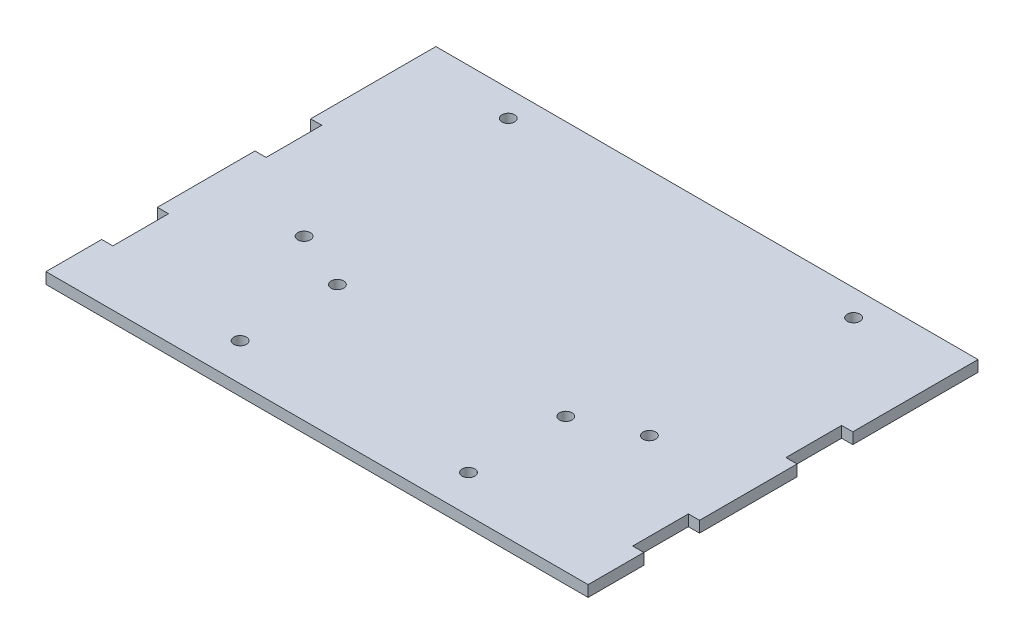
SolidWorks part; units mm, degrees
other "Markup1"
sketch "Sketch3" plane through (-73, 3, -52.5) normal (0, 1, 0) x (1, 0, 0)
ref_plane "Front Plane" through (0, 0, 0) normal (0, 0, 1) x (1, 0, 0)
ref_plane "Top Plane" through (0, 0, 0) normal (0, 1, 0) x (1, 0, 0)
ref_plane "Right Plane" through (0, 0, 0) normal (1, 0, 0) x (0, 0, -1)
other "Configuration Table"
sketch "Sketch1" plane through (0, 0, 0) normal (0, 1, 0) x (1, 0, 0)
  line L1 (73, -52.5) -> (-73, -52.5)
  line L2 (73, -52.5) -> (73, 52.5)
  line L3 (73, 52.5) -> (-73, 52.5)
  line L4 (-73, -52.5) -> (-73, 52.5)
  line L5 (73, -52.5) -> (-73, 52.5) construction
  line L6 (73, 52.5) -> (-73, -52.5) construction
  point P0 (0, 0)
  dimension "D1" = 105
  dimension "D2" = 146
extrude "Boss-Extrude1" add sketch "Sketch1" along normal blind 3
sketch "Sketch2" plane through (0, 3, 0) normal (0, 1, 0) x (1, 0, 0)
  line L0 (73, 52.5) -> (-73, 52.5) construction
  line L1 (-73, -37.5) -> (-70, -37.5)
  line L2 (-73, 52.5) -> (-73, -52.5) construction
  line L3 (-70, -37.5) -> (-70, -22.5)
  line L4 (-70, -22.5) -> (-73, -22.5)
  line L5 (-73, -22.5) -> (-73, -37.5)
  line L6 (-73, 3.77) -> (-70, 3.77)
  line L7 (-70, 3.77) -> (-70, 18.77)
  line L8 (-70, 18.77) -> (-73, 18.77)
  line L9 (-73, 18.77) -> (-73, 3.77)
  line L10 (73, 18.77) -> (70, 18.77)
  line L11 (73, -52.5) -> (73, 52.5) construction
  line L12 (70, 18.77) -> (70, 3.77)
  line L13 (70, 3.77) -> (73, 3.77)
  line L14 (73, 3.77) -> (73, 18.77)
  line L15 (73, -22.5) -> (70, -22.5)
  line L16 (70, -22.5) -> (70, -37.5)
  line L17 (70, -37.5) -> (73, -37.5)
  line L18 (73, -37.5) -> (73, -22.5)
  circle A0 centre (-46.5, 45.5) radius 1.7
  circle A1 centre (46.5, 45.5) radius 1.7
  circle A2 centre (46.5, -9.5) radius 1.7
  circle A3 centre (-46.5, -9.5) radius 1.7
  circle A4 centre (-30.75, -16.2784) radius 1.7
  circle A5 centre (30.75, -16.2784) radius 1.7
  circle A6 centre (30.75, -42.4784) radius 1.7
  circle A7 centre (-30.75, -42.4784) radius 1.7
  dimension "D1" = 93
  dimension "D5" = 30.75
  dimension "D2" = 46.5
  dimension "D3" = 55
  dimension "D4" = 7
  dimension "D6" = 30.75
  dimension "D7" = 26.2
  dimension "D8" = 3
  dimension "D9" = 15
  dimension "D10" = 15
  dimension "D11" = 26.27
  dimension "D12" = 15
extrude "Cut-Extrude1" cut sketch "Sketch2" against normal blind 3
